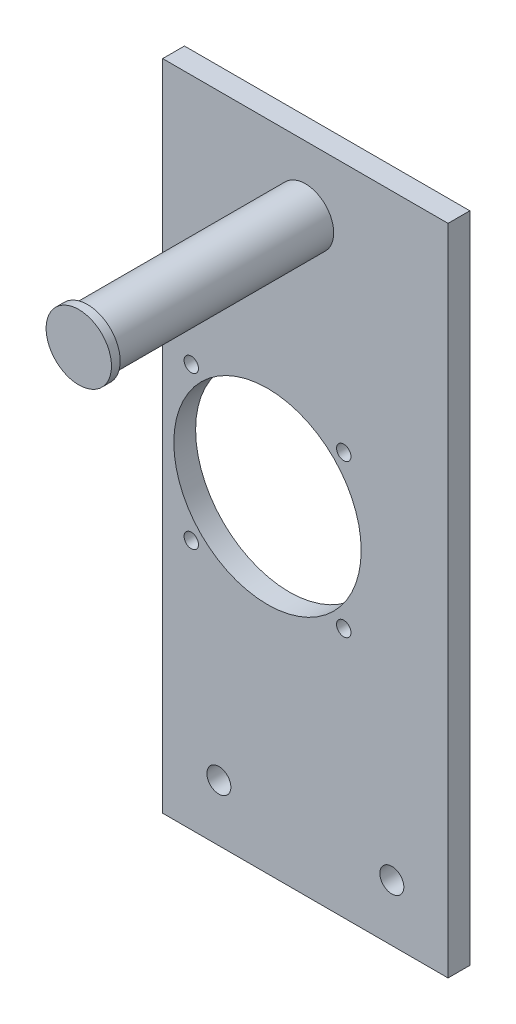
SolidWorks part; units mm, degrees
ref_plane "Plan de face" through (0, 0, 0) normal (0, 0, 1) x (1, 0, 0)
ref_plane "Plan de dessus" through (0, 0, 0) normal (0, 1, 0) x (1, 0, 0)
ref_plane "Plan de droite" through (0, 0, 0) normal (1, 0, 0) x (0, 0, -1)
sketch "Sketch1" plane through (0, 0, 0) normal (0, 0, 1) x (1, 0, 0)
  line L1 (32.75, -75) -> (-32.75, -75)
  line L2 (32.75, -75) -> (32.75, 75)
  line L3 (32.75, 75) -> (-32.75, 75)
  line L4 (-32.75, -75) -> (-32.75, 75)
  line L5 (32.75, -75) -> (-32.75, 75) construction
  line L6 (32.75, 75) -> (-32.75, -75) construction
  circle A0 centre (-19.85, -62) radius 2.75
  circle A1 centre (19.85, -62) radius 2.75
  point P0 (0, 0)
  dimension "D5" = 5.5
  dimension "D1" = 65.5
  dimension "D2" = 39.7
  dimension "D3" = 12.9
  dimension "D4" = 13
  dimension "D6" = 150
extrude "Boss-Extrude1" add sketch "Sketch1" along normal blind 5
sketch "Sketch2" plane through (0, 0, 5) normal (0, 0, 1) x (1, 0, 0)
  line L0 (32.75, 75) -> (-32.75, 75) construction
  circle A0 centre (0, 60) radius 6.5
  dimension "D1" = 13
  dimension "D2" = 15
extrude "Boss-Extrude2" add sketch "Sketch2" along normal blind 50
sketch "Sketch3" plane through (0, 0, 55) normal (0, 0, 1) x (1, 0, 0)
  circle A0 centre (0, 60) radius 7.5
  dimension "D1" = 15
extrude "Boss-Extrude3" add sketch "Sketch3" along normal blind 2
sketch "Sketch4" plane through (0, 0, 0) normal (0, 0, -1) x (-1, 0, 0)
  line L1 (-8.8129, 17.5) -> (26.1871, 17.5) construction
  line L2 (-8.8129, 17.5) -> (-8.8129, -17.5) construction
  line L3 (-8.8129, -17.5) -> (26.1871, -17.5) construction
  line L4 (26.1871, 17.5) -> (26.1871, -17.5) construction
  line L5 (-8.8129, 17.5) -> (26.1871, -17.5) construction
  line L6 (-8.8129, -17.5) -> (26.1871, 17.5) construction
  circle A0 centre (26.1871, 17.5) radius 1.65
  circle A1 centre (-8.8129, 17.5) radius 1.65
  circle A2 centre (-8.8129, -17.5) radius 1.65
  circle A3 centre (26.1871, -17.5) radius 1.65
  circle A4 centre (8.6871, 0) radius 21.5
  point P0 (8.6871, 0)
  dimension "D3" = 3.3
  dimension "D4" = 43
  dimension "D1" = 35
  dimension "D2" = 35
extrude "Cut-Extrude1" cut sketch "Sketch4" against normal through all
